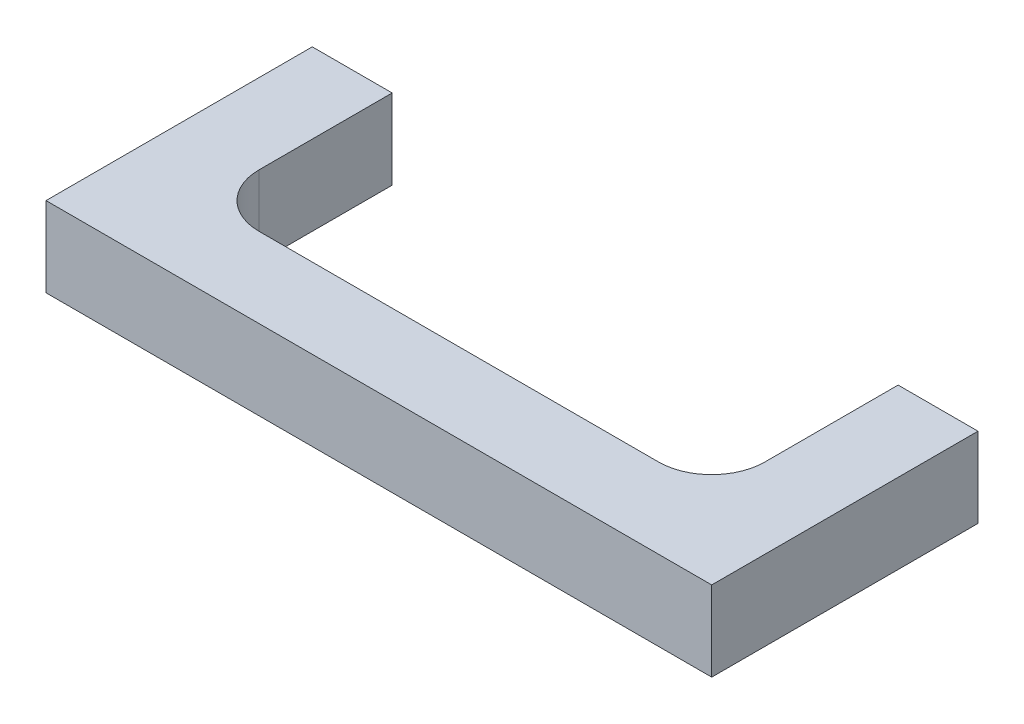
SolidWorks part; units mm, degrees
ref_plane "Alzado" through (0, 0, 0) normal (0, 0, 1) x (1, 0, 0)
ref_plane "Planta" through (0, 0, 0) normal (0, 1, 0) x (1, 0, 0)
ref_plane "Vista lateral" through (0, 0, 0) normal (1, 0, 0) x (0, 0, -1)
sketch "Croquis1" plane through (0, 0, 0) normal (0, 1, 0) x (1, 0, 0)
  line L0 (12.5, 0) -> (-12.5, 0)
  line L1 (-12.5, 0) -> (-12.5, 10)
  line L2 (-12.5, 10) -> (-9.5, 10)
  line L3 (-9.5, 10) -> (-9.5, 3)
  line L4 (-9.5, 3) -> (9.5, 3)
  line L5 (0, 0) -> (0, 15.9586) construction
  line L6 (12.5, 0) -> (12.5, 10)
  line L7 (12.5, 10) -> (9.5, 10)
  line L8 (9.5, 10) -> (9.5, 3)
  point P10 (0, 3)
  dimension "D1" = 10
  dimension "D2" = 12.5
  dimension "D4" = 3
extrude "Saliente-Extruir1" add sketch "Croquis1" against normal blind 3
fillet "Redondeo4" radius 2 1 edges at (-9.5, -1.5, -3)
fillet "Redondeo5" radius 2 1 edges at (9.5, -1.5, -3)
